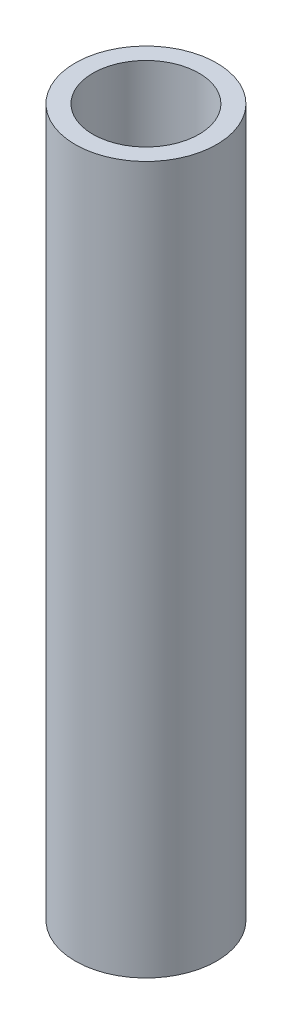
SolidWorks part; units mm, degrees
ref_plane "Front Plane" through (0, 0, 0) normal (0, 0, 1) x (1, 0, 0)
ref_plane "Top Plane" through (0, 0, 0) normal (0, 1, 0) x (1, 0, 0)
ref_plane "Right Plane" through (0, 0, 0) normal (1, 0, 0) x (0, 0, -1)
sketch "Sketch1" plane through (0, 0, 0) normal (0, 1, 0) x (1, 0, 0)
  circle A0 centre (0, 0) radius 2
extrude "Boss-Extrude1" add sketch "Sketch1" along normal blind 20
sketch "Sketch3" plane through (0, 20, 0) normal (0, 1, 0) x (1, 0, 0)
  circle A0 centre (0, 0) radius 1.5
extrude "Cut-Extrude1" cut sketch "Sketch3" against normal blind 3
